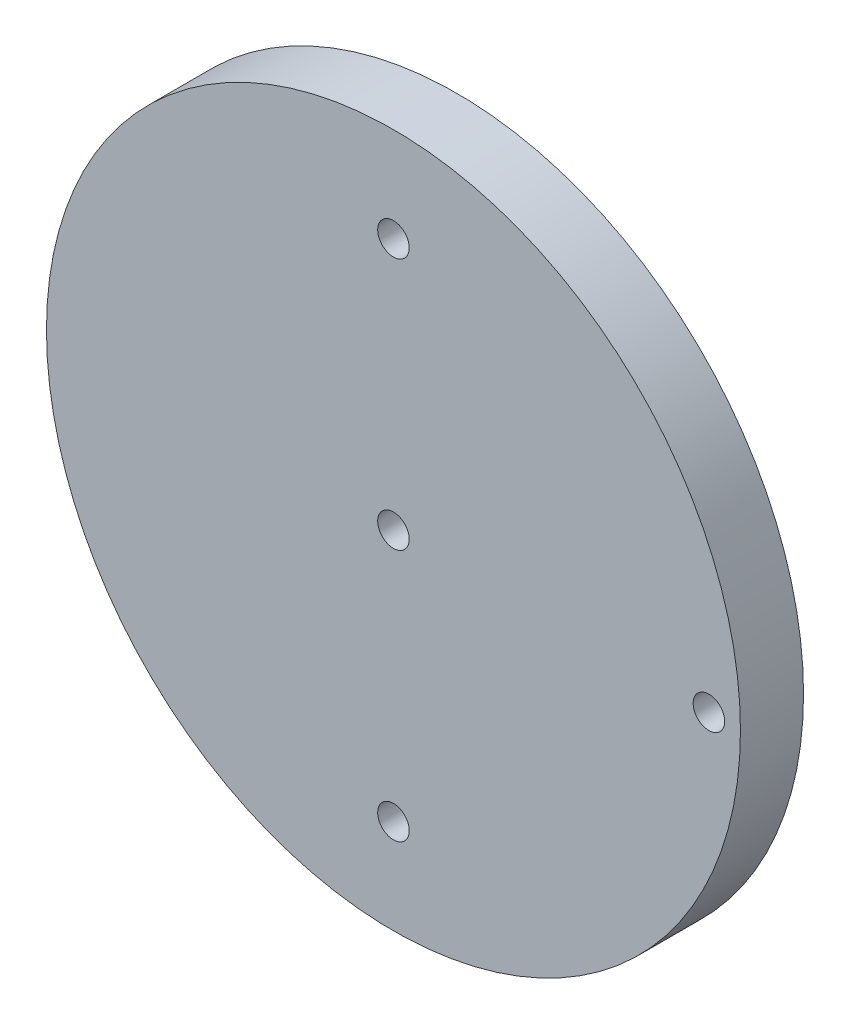
SolidWorks part; units mm, degrees
ref_plane "前视基准面" through (0, 0, 0) normal (0, 0, 1) x (1, 0, 0)
ref_plane "上视基准面" through (0, 0, 0) normal (0, 1, 0) x (1, 0, 0)
ref_plane "右视基准面" through (0, 0, 0) normal (1, 0, 0) x (0, 0, -1)
sketch "草图1" plane through (0, 0, 0) normal (0, 0, 1) x (1, 0, 0)
  circle A0 centre (0, 0) radius 55
extrude "凸台-拉伸1" add sketch "草图1" along normal blind 10
sketch "草图2" plane through (0, 0, 10) normal (0, 0, 1) x (1, 0, 0)
  line L0 (0, 0) -> (50, 0)
  circle A0 centre (0, 0) radius 2.5
  circle A1 centre (50, 0) radius 2.5
extrude "切除-拉伸1" cut sketch "草图2" against normal through all
sketch "草图4" plane through (0, 0, 0) normal (0, 0, -1) x (-1, 0, 0)
  line L0 (0, 0) -> (-50, 0)
  circle A0 centre (0, -40) radius 2.5
  circle A1 centre (0, 40) radius 2.5
  point P8 (0, 0)
  point P9 (0, 0)
extrude "切除-拉伸2" cut sketch "草图4" against normal through all contours A0 | A1
